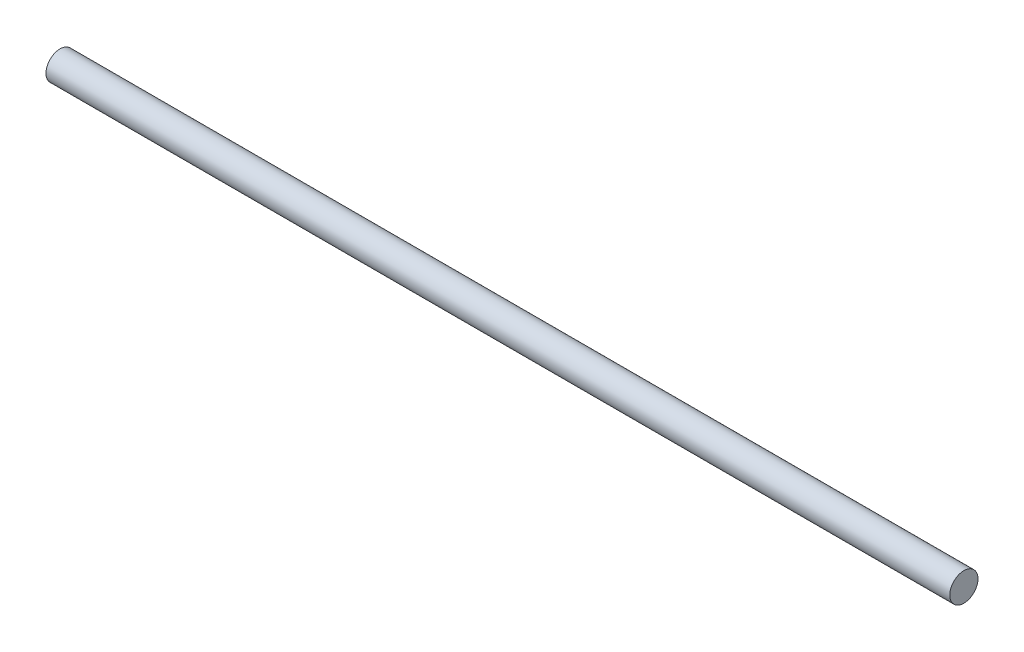
SolidWorks part; units mm, degrees
material "6061-T6 (SS)"
ref_plane "Front Plane" through (0, 0, 0) normal (0, 0, 1) x (1, 0, 0)
ref_plane "Top Plane" through (0, 0, 0) normal (0, 1, 0) x (1, 0, 0)
ref_plane "Right Plane" through (0, 0, 0) normal (1, 0, 0) x (0, 0, -1)
sketch "Sketch1" plane through (0, 0, 0) normal (1, 0, 0) x (0, 0, -1)
  circle A0 centre (0, 0) radius 6.35
  dimension "D1" = 12.7
extrude "Boss-Extrude1" add sketch "Sketch1" along normal blind 406.4
